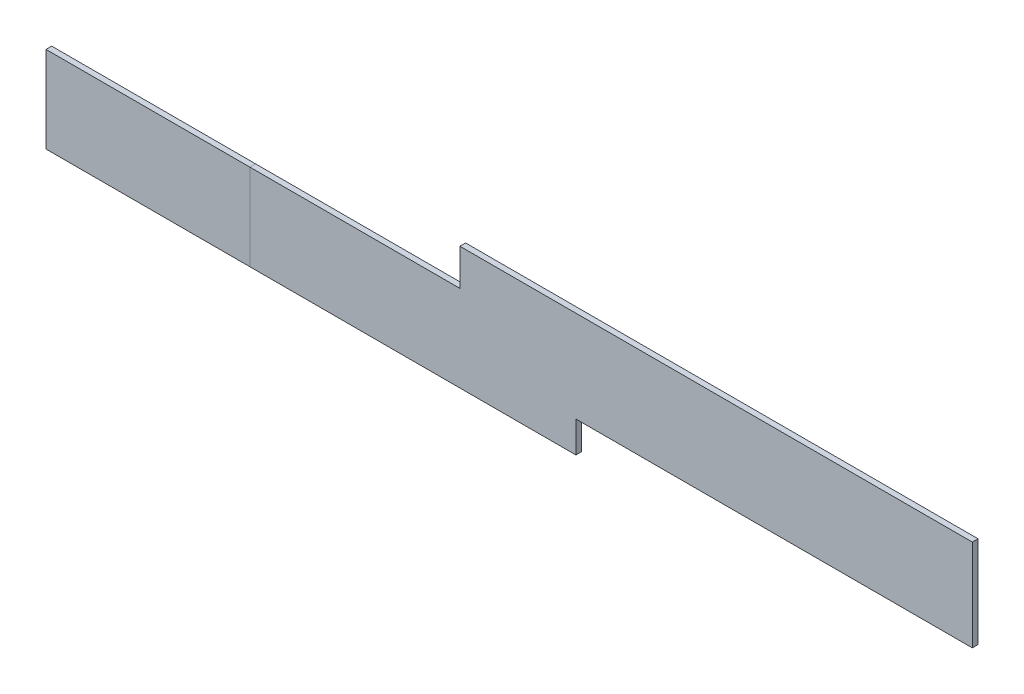
SolidWorks part; units mm, degrees
material "Custom Plastic"
ref_plane "X-Y Datum" through (0, 0, 0) normal (0, 0, 1) x (1, 0, 0)
ref_plane "X-Z Datum" through (0, 0, 0) normal (0, 1, 0) x (1, 0, 0)
ref_plane "Y-Z Datum" through (0, 0, 0) normal (1, 0, 0) x (0, 0, -1)
sketch "Sketch1" plane through (0, 0, 0) normal (0, 0, 1) x (1, 0, 0)
  line L0 (0, 48.0314) -> (0, 0)
  line L1 (0, 0) -> (172.1129, 0)
  line L2 (0, 0) -> (0, 68.3514) construction
  line L3 (0, 68.3514) -> (172.1129, 68.3514) construction
  line L4 (172.1129, 0) -> (172.1129, 68.3514)
  line L5 (86.0565, 68.3514) -> (86.0565, 0) construction
  line L6 (0, 34.1757) -> (172.1129, 34.1757) construction
  line L7 (0, 68.3514) -> (116.84, 68.3514) construction
  line L8 (0, 68.3514) -> (0, 48.0314) construction
  line L9 (0, 48.0314) -> (116.84, 48.0314)
  line L10 (116.84, 68.3514) -> (116.84, 48.0314)
  line L11 (58.42, 48.0314) -> (58.42, 68.3514) construction
  line L12 (0, 58.1914) -> (116.84, 58.1914) construction
  line L13 (116.84, 68.3514) -> (172.1129, 68.3514)
  point P148 (86.0565, 34.1757)
  point P257 (58.42, 58.1914)
  dimension "D1" = 68.3514
  dimension "D2" = 172.1129
  dimension "D3" = 20.32
  dimension "D4" = 116.84
extrude "Boss-Extrude1" add sketch "Sketch1" against normal blind 3.175
sketch "Sketch2" plane through (0, 0, 0) normal (0, 0, 1) x (1, 0, 0)
  line L0 (0, 0) -> (172.1129, 0) construction
  line L1 (0, 48.0314) -> (-113.538, 48.0314)
  line L2 (0, 48.0314) -> (0, 0)
  line L3 (0, 0) -> (-113.538, 0)
  line L4 (-113.538, 48.0314) -> (-113.538, 0)
  line L5 (-56.769, 0) -> (-56.769, 48.0314) construction
  line L6 (0, 24.0157) -> (-113.538, 24.0157) construction
  point P244 (-56.769, 24.0157)
  dimension "D1" = 113.538
extrude "Boss-Extrude2" add sketch "Sketch2" against normal up to surface (3.175 mm away) separate body up to face at (96.3176, 38.7943, -3.175)
sketch "Sketch3" plane through (0, 0, 0) normal (0, 0, 1) x (1, 0, 0)
  line L0 (0, 0) -> (172.1129, 0) construction
  line L1 (172.1129, 68.3514) -> (297.5381, 68.3514)
  line L2 (172.1129, 68.3514) -> (172.1129, 0)
  line L3 (172.1129, 0) -> (297.5381, 0) construction
  line L4 (297.5381, 68.3514) -> (297.5381, 0) construction
  line L5 (234.8255, 0) -> (234.8255, 68.3514) construction
  line L6 (172.1129, 34.1757) -> (297.5381, 34.1757) construction
  line L7 (297.5381, 68.3514) -> (297.5381, 17.338)
  line L8 (297.5381, 0) -> (181.3992, 0) construction
  line L9 (297.5381, 0) -> (297.5381, 17.338) construction
  line L10 (297.5381, 17.338) -> (181.3992, 17.338)
  line L11 (181.3992, 0) -> (181.3992, 17.338)
  line L12 (239.4687, 17.338) -> (239.4687, 0) construction
  line L13 (297.5381, 8.669) -> (181.3992, 8.669) construction
  line L14 (172.1129, 0) -> (181.3992, 0)
  point P149 (239.4687, 8.669)
  point P268 (234.8255, 34.1757)
  dimension "D1" = 125.4252
  dimension "D2" = 17.338
  dimension "D3" = 9.2862
extrude "Boss-Extrude3" add sketch "Sketch3" against normal up to surface (3.175 mm away) up to face at (96.3176, 38.7943, -3.175)
sketch "Sketch4" plane through (0, 0, 0) normal (0, 0, 1) x (1, 0, 0)
  line L0 (181.3992, 17.338) -> (297.5381, 17.338) construction
  line L1 (297.5381, 68.3514) -> (402.0337, 68.3514)
  line L2 (297.5381, 68.3514) -> (297.5381, 17.338)
  line L3 (297.5381, 17.338) -> (402.0337, 17.338)
  line L4 (402.0337, 68.3514) -> (402.0337, 17.338)
  line L5 (349.7859, 17.338) -> (349.7859, 68.3514) construction
  line L6 (297.5381, 42.8447) -> (402.0337, 42.8447) construction
  point P180 (349.7859, 42.8447)
  dimension "D1" = 104.4956
extrude "Boss-Extrude4" add sketch "Sketch4" against normal up to surface (3.175 mm away) up to face at (148.9443, 33.4302, -3.175)
